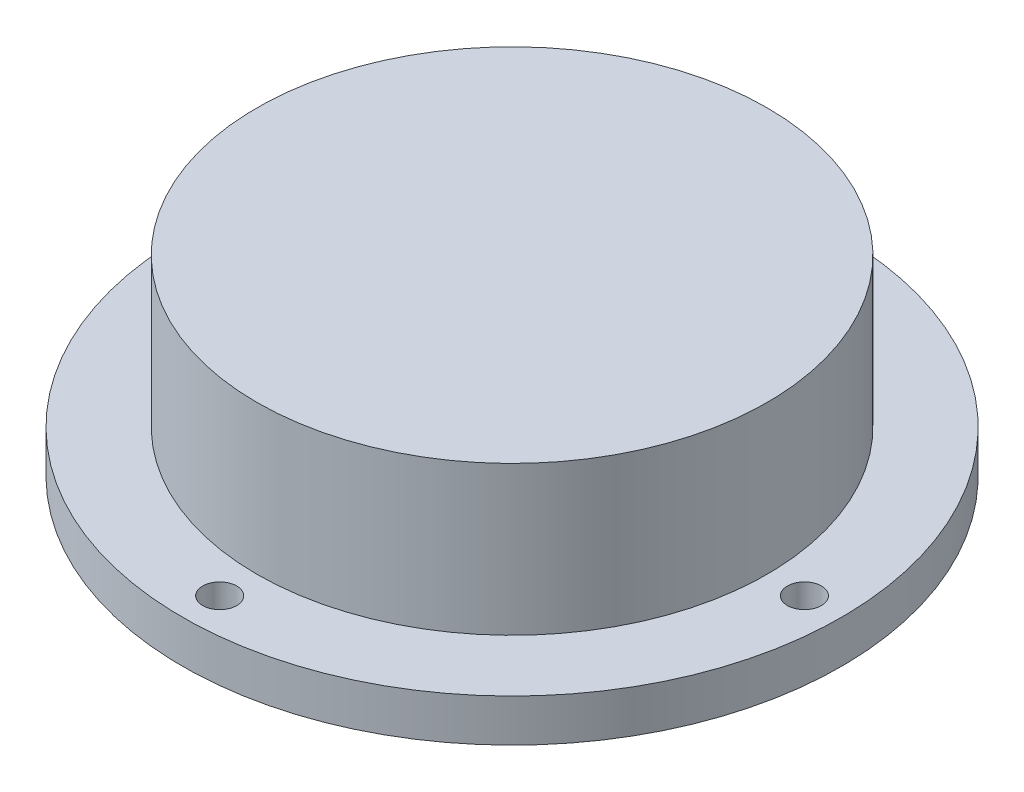
SolidWorks part; units mm, degrees
ref_plane "Front Plane" through (0, 0, 0) normal (0, 0, 1) x (1, 0, 0)
ref_plane "Top Plane" through (0, 0, 0) normal (0, 1, 0) x (1, 0, 0)
ref_plane "Right Plane" through (0, 0, 0) normal (1, 0, 0) x (0, 0, -1)
sketch "Sketch1" plane through (0, 0, 0) normal (0, 1, 0) x (1, 0, 0)
  circle A0 centre (0, 0) radius 24
extrude "Boss-Extrude1" add sketch "Sketch1" along normal blind 14
sketch "Sketch2" plane through (0, 0, 0) normal (0, -1, 0) x (1, 0, 0)
  circle A0 centre (0, 0) radius 19.5
extrude "Cut-Extrude1" cut sketch "Sketch2" against normal blind 10
sketch "Sketch3" plane through (0, 10, 0) normal (0, -1, 0) x (1, 0, 0)
  circle A0 centre (0, 0) radius 6
extrude "Cut-Extrude2" cut sketch "Sketch3" against normal blind 1.5
sketch "Sketch4" plane through (0, 0, 0) normal (0, -1, 0) x (1, 0, 0)
  circle A0 centre (0, 0) radius 31
extrude "Boss-Extrude2" add sketch "Sketch4" along normal blind 4
sketch "Sketch5" plane through (0, -4, 0) normal (0, -1, 0) x (1, 0, 0)
  circle A0 centre (0, 0) radius 19.5
extrude "Cut-Extrude3" cut sketch "Sketch5" against normal blind 4
sketch "Sketch6" plane through (0, 0, 0) normal (0, 1, 0) x (1, 0, 0)
  circle A0 centre (0, 0) radius 27.5
hole_wizard "Ø3.2 (3.2) Diameter Hole1" positions "Sketch7" profile "Sketch8" hole size "Ø3.2" standard "ISO" end condition through all
sketch "Sketch7" plane through (0, 0, 0) normal (0, 1, 0) x (1, 0, 0)
  circle A0 centre (0, 0) radius 27.5 construction
  point P0 (-27.5, 0)
  point P4 (0, 27.5)
  point P6 (27.5, 0)
  point P8 (0, -27.5)
sketch "Sketch8" plane through (-27.5, 0, 0) normal (1, 0, 0) x (0, 0, 1)
  line L0 (0, 0) -> (0, 4)
  line L1 (0, 4) -> (1.6, 4)
  line L2 (1.6, 4) -> (1.6, 0)
  line L5 (1.6, 0) -> (0, 0)
  line L11 (0, -6.35) -> (0, 107.95) construction
  dimension "Thru Hole Dia." = 3.2
  dimension "Thru Hole Depth" = 4
